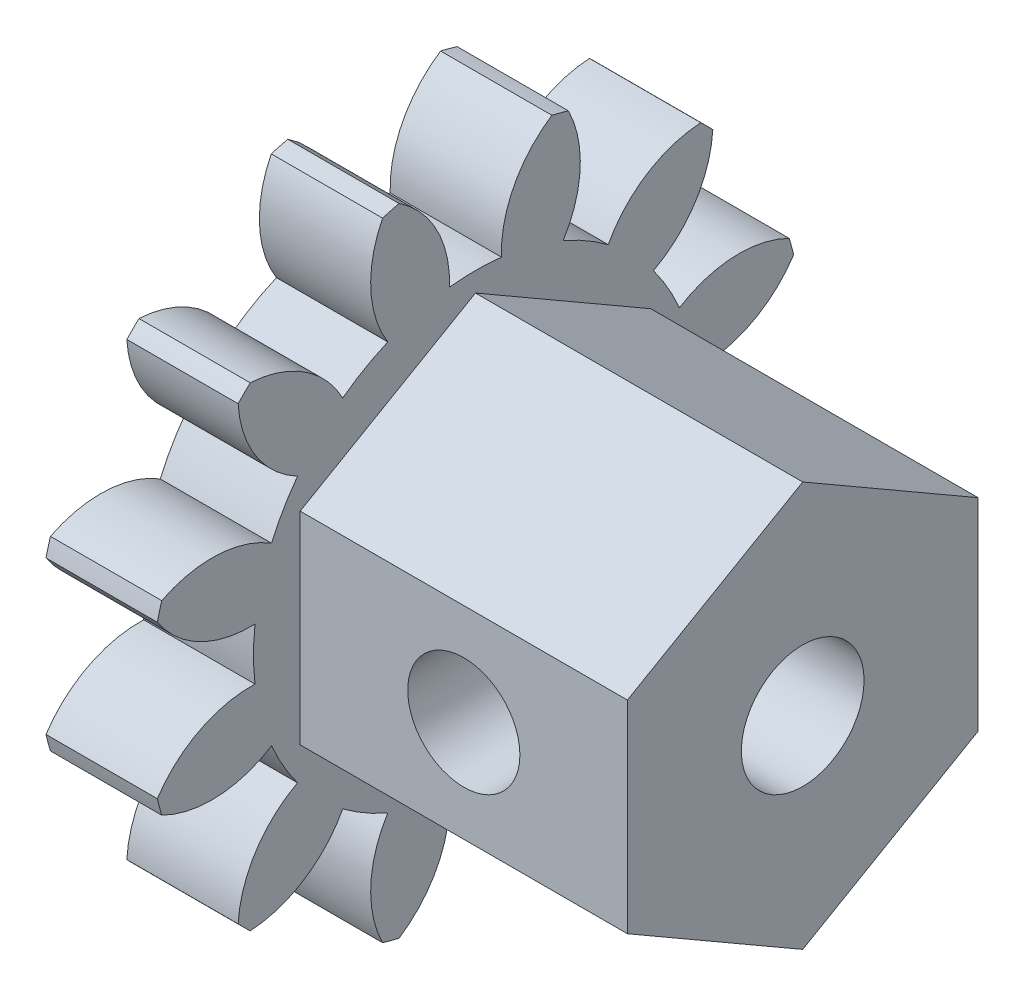
SolidWorks part; units mm, degrees
ref_plane "Plane1" through (0, 0, 0) normal (0, 0, 1) x (1, 0, 0)
ref_plane "Plane2" through (0, 0, 0) normal (0, 1, 0) x (1, 0, 0)
ref_plane "Plane3" through (0, 0, 0) normal (1, 0, 0) x (0, 0, -1)
sketch "HoldingSke" plane through (0, 0, 0) normal (0, 1, 0) x (1, 0, 0)
  line L0 (0, 0) -> (0.4891, -0.104)
  line L1 (-15, 0) -> (100, 0) construction
  line L2 (0, 0) -> (-2.1039, 2.3779)
  line L3 (0, 0) -> (-11.863, 4.5341)
  line L4 (0, 0) -> (8.4473, 1.7955)
  line L5 (0, 0) -> (-46.8476, -17.4728)
  line L6 (0, 0) -> (-3.9479, -2.6637)
  line L7 (-2.1039, 2.3779) -> (8.6586, 51.2059)
  line L8 (-76.2, 54.61) -> (-74.4, 54.61)
  line L9 (-71.009, 38.7566) -> (-53.1078, 45.2721)
  line L10 (-76.2, 71.12) -> (104.1128, 71.12)
  line L11 (0, 0) -> (-4.7625, 0)
  line L12 (-76.2, 101.6) -> (-76.133, 101.6)
  line L13 (24.9733, 27.94) -> (52.9518, 28.4284)
  line L14 (24.9733, 27.94) -> (24.9743, 27.94)
  line L15 (24.9733, 27.94) -> (100.4006, 29.5858)
  line L16 (-63.627, -2) -> (-12.827, -2)
  circle A0 centre (0, 0) radius 5
  circle A1 centre (0, 0) radius 9.499
  circle A2 centre (0, 0) radius 37.5
  circle A3 centre (0, 0) radius 5
  dimension "MHD" = 18.998
  dimension "Hub_dia" = 75
  dimension "Bore" = 10
  dimension "MBD" = 10
  dimension "Num_teeth" = 12
  dimension "Pitch_radius" = 180.3128
  dimension "Pitch" = 0.5
  dimension "Width" = 4.7625
  dimension "Overall_len" = 50
  dimension "Show_teeth" = 12
  dimension "Thickness" = 4.7625
  dimension "OAL" = 50.0001
  dimension "T_dim" = 1.8
  dimension "Ap" = 20
  dimension "H" = 19.05
  dimension "Backlash" = 0.067
  dimension "Addendum_fac" = 1
  dimension "Dedendum_fac" = 1.25
  dimension "Clearance_fac" = 0.25
  dimension "Dedendum_add" = 0.001
  dimension "Module" = 2
sketch "BasProSke" plane through (0, 0, 0) normal (0, 1, 0) x (1, 0, 0)
  line L0 (-10, 0) -> (60, 0) construction
  line L1 (0, 0) -> (0, 14)
  line L2 (0, 0) -> (4.7625, 0)
  line L3 (4.7625, 0) -> (4.7625, 14)
  line L4 (4.7625, 14) -> (0, 14)
  dimension "Diameter" = 28
  dimension "Thickness" = 4.7625
revolve "Base-Revolve" add sketch "BasProSke" angle 360 about L0
sketch "TooCutSke" plane through (0, 0, 0) normal (1, 0, 0) x (0, 0, -1)
  line L1 (0, 0) -> (0, 107) construction
  line L2 (0, 0) -> (-1.6834, 11.8813) construction
  line L3 (0, 0) -> (-6.1662, 23.0126) construction
  line L4 (-1.6834, 11.8813) -> (-3.0831, 11.5063) construction
  arc A0 (1.1119, 9.4337) -> (-1.1119, 9.4337) centre (0, 0) ccw
  arc A1 (3.2981, 13.6321) -> (-3.2981, 13.6321) centre (0, 0) ccw
  circle A2 centre (0, 0) radius 12 construction
  circle A3 centre (0, 0) radius 11.2763 construction
  arc A4 (-1.1119, 9.4337) -> (-3.2981, 13.6321) centre (-5.9089, 9.6042) ccw
  arc A5 (3.2981, 13.6321) -> (1.1119, 9.4337) centre (5.9089, 9.6042) ccw
  dimension "Root_dia" = 18.998
  dimension "Overcut_dia" = 28.0508
  dimension "Pitch_dia" = 24
  dimension "Base_dia" = 22.5526
  dimension "Flank_rad" = 4.8
  dimension "Half_ang" = 15
  dimension "Half_CT" = 1.4491
extrude "ToothCut" cut sketch "TooCutSke" along normal through all
fillet "Breaks" [suppressed] radius 0.04
fillet "RootFillets" [suppressed] radius 0.501
pattern_circular "TeethCuts" count 12 every 30 about axis through (-10, 0, 0) along (1, 0, 0) of "ToothCut", "RootFillets", "Breaks"
sketch "HubNeaOneSke" plane through (0, 0, 0) normal (-1, 0, 0) x (0, 0, 1)
  circle A0 centre (0, 0) radius 9.499
  dimension "Diameter" = 18.998
extrude "HubNearOne" [suppressed] add sketch "HubNeaOneSke" along normal blind 45.2376
sketch "HubNeaBotSke" plane through (0, 0, 0) normal (-1, 0, 0) x (0, 0, 1)
  circle A0 centre (0, 0) radius 9.499
  dimension "Diameter" = 18.998
extrude "HubNearBoth" [suppressed] add sketch "HubNeaBotSke" along normal blind 22.6188
ref_plane "FarPln" through (4.7625, 0, 0) normal (1, 0, 0) x (0, 0, -1)
sketch "HubFarSke" plane through (4.7625, 0, 0) normal (1, 0, 0) x (0, 0, -1)
  circle A0 centre (0, 0) radius 9.499
  dimension "Diameter" = 18.998
extrude "HubFar" [suppressed] add sketch "HubFarSke" along normal blind 22.6188
sketch "BorSke" plane through (0, 0, 0) normal (1, 0, 0) x (0, 0, -1)
  circle A0 centre (0, 0) radius 2.625
  dimension "Diameter" = 5.25
extrude "Bore" cut sketch "BorSke" along normal mid plane 100.0001
sketch "KeySke" plane through (0, 0, 0) normal (1, 0, 0) x (0, 0, -1)
  line L0 (-2, 0) -> (-2, 6.8)
  line L1 (-2, 6.8) -> (2, 6.8)
  line L2 (2, 6.8) -> (2, 0)
  line L3 (0, 0) -> (0, 34) construction
  line L4 (-2, 0) -> (2, 0)
  dimension "Offset" = 6.8
  dimension "Width" = 4
extrude "Keyway" [suppressed] cut sketch "KeySke" along normal mid plane 100.0001
pattern_circular "Keyway2" [suppressed] count 2 every 90 about axis through (-10, 0, 0) along (1, 0, 0)
sketch "Sketch1" plane through (4.7625, 0, 0) normal (1, 0, 0) x (0, 0, -1)
  line L1 (0, 8.6603) -> (-7.5, 4.3301)
  line L2 (-7.5, 4.3301) -> (-7.5, -4.3301)
  line L3 (-7.5, -4.3301) -> (0, -8.6603)
  line L4 (0, -8.6603) -> (7.5, -4.3301)
  line L5 (7.5, -4.3301) -> (7.5, 4.3301)
  line L6 (7.5, 4.3301) -> (0, 8.6603)
  circle A0 centre (0, 0) radius 7.5 construction
  dimension "D1" = 15
extrude "Boss-Extrude1" add sketch "Sketch1" along normal blind 14
sketch "Sketch2" plane through (18.7625, 0, 0) normal (1, 0, 0) x (0, 0, -1)
  circle A0 centre (0, 0) radius 2.625 construction
  circle A1 centre (0, 0) radius 2.625
extrude "Cut-Extrude1" cut sketch "Sketch2" against normal through all
sketch "Sketch3" plane through (0, 0, 7.5) normal (0, 0, 1) x (1, 0, 0)
  line L0 (18.7625, 0) -> (4.7625, 0) construction
  line L3 (18.7625, 4.3301) -> (18.7625, -4.3301) construction
  line L4 (4.7625, -1.1119) -> (4.7625, 1.1119) construction
  circle A0 centre (11.7625, 0) radius 2.4
  dimension "D1" = 4.8
extrude "Cut-Extrude2" cut sketch "Sketch3" against normal through all
equation "' \"Module@HoldingSke\" = 6.35"
equation "' \"Num_teeth@HoldingSke\" = 12"
equation "' \"Ap@HoldingSke\" =  20"
equation "' \"Width@HoldingSke\" = 0.5 * 25.4"
equation "' \"Hub_dia@HoldingSke\"= 1 * 25.4"
equation "' \"Overall_len@HoldingSke\" = 1.0 * 25.4"
equation "' \"Bore@HoldingSke\" = 0.75 * 25.4"
equation "' \"T_dim@HoldingSke\" = 0.1 * 25.4"
equation "' \"Width@KeySke\" = 0.25 * 25.4"
equation "' \"Show_teeth@HoldingSke\" = 13"
equation "' \"Backlash@HoldingSke\" = 0.009 * 25.4"
equation "' \"Addendum_fac@HoldingSke\" = 1.0"
equation "' \"Dedendum_fac@HoldingSke\" = 1.25"
equation "' \"Dedendum_add@HoldingSke\" = 0.00005 * 25.4"
equation "' \"Clearance_fac@HoldingSke\" = 0.25"
equation "\"Pitch@HoldingSke\" = 1 / \"Module@HoldingSke\""
equation "\"Overcut_dia@TooCutSke\" = (\"Num_teeth@HoldingSke\" + 2 * \"Addendum_fac@HoldingSke\") / \"Pitch@HoldingSke\" + 0.002 * 25.4"
equation "\"Pitch_dia@TooCutSke\" = \"Num_teeth@HoldingSke\" / \"Pitch@HoldingSke\""
equation "\"Base_dia@TooCutSke\" = \"Num_teeth@HoldingSke\" / \"Pitch@HoldingSke\" * cos((\"Ap@HoldingSke\"  * 3.14159265 / 180))"
equation "\"Root_dia@TooCutSke\" = (\"Num_teeth@HoldingSke\" + 2) / \"Pitch@HoldingSke\" - 2 * (\"Addendum_fac@HoldingSke\" + \"Dedendum_fac@HoldingSke\") / \"Pitch@HoldingSke\" - \"Dedendum_add@HoldingSke\" * 2"
equation "\"Half_ang@TooCutSke\" = 180 / \"Num_teeth@HoldingSke\""
equation "\"Half_CT@TooCutSke\" = \"Num_teeth@HoldingSke\" / \"Pitch@HoldingSke\" * sin((3.14159265 / 2 / \"Num_teeth@HoldingSke\")) / 2 - 7 * \"Backlash@HoldingSke\" / 4"
equation "\"Flank_rad@TooCutSke\" = \"Num_teeth@HoldingSke\" / \"Pitch@HoldingSke\" / 5"
equation "\"Radius@RootFillets\" = \"Clearance_fac@HoldingSke\" / \"Pitch@HoldingSke\" + \"Dedendum_add@HoldingSke\""
equation "\"Break_rad@Breaks\" = 0.02 / \"Pitch@HoldingSke\""
equation "\"Thickness@HoldingSke\" = \"Width@HoldingSke\""
equation "\"OAL@HoldingSke\" = \"Thickness@HoldingSke\""
equation "\"MHD@HoldingSke\" = (\"Num_teeth@HoldingSke\" + 2) / \"Pitch@HoldingSke\" - 2 * (\"Addendum_fac@HoldingSke\" + \"Dedendum_fac@HoldingSke\")  / \"Pitch@HoldingSke\" - \"Dedendum_add@HoldingSke\" * 2"
equation "\"MBD@HoldingSke\" = (\"Num_teeth@HoldingSke\" + 2) / \"Pitch@HoldingSke\" - 2 * (\"Addendum_fac@HoldingSke\" + \"Dedendum_fac@HoldingSke\")  / \"Pitch@HoldingSke\" - \"Dedendum_add@HoldingSke\" * 2 - 0.002 * 25.4"
equation "\"MHD@HoldingSke\" = ((sgn( \"MHD@HoldingSke\" - \"Hub_dia@HoldingSke\" )-1)*( \"MHD@HoldingSke\" - \"Hub_dia@HoldingSke\" ))/-2+ \"Hub_dia@HoldingSke\""
equation "\"MBD@HoldingSke\" = ((sgn( \"MBD@HoldingSke\" - \"Bore@HoldingSke\" )-1)*( \"MBD@HoldingSke\" - \"Bore@HoldingSke\" ))/-2+ \"Bore@HoldingSke\""
equation "\"OAL@HoldingSke\" = ((sgn( \"OAL@HoldingSke\" - \"Overall_len@HoldingSke\" )+1)*( \"OAL@HoldingSke\" - \"Overall_len@HoldingSke\" ))/2 + \"Overall_len@HoldingSke\" + 0.000002 * 25.4"
equation "\"Num_teeth@TeethCuts\" = int( \"Show_teeth@HoldingSke\" ) + 1"
equation "\"Num_teeth@TeethCuts\" = ((sgn( \"Num_teeth@TeethCuts\" - \"Num_teeth@HoldingSke\" )-1)*( \"Num_teeth@TeethCuts\" - \"Num_teeth@HoldingSke\" ))/-2+ \"Num_teeth@HoldingSke\""
equation "\"Num_teeth@TeethCuts\" = ((sgn( \"Num_teeth@TeethCuts\" - 2.0)+1)*( \"Num_teeth@TeethCuts\" - 2.0))/2 +2.0"
equation "\"Angle@TeethCuts\" = 360.0 / \"Num_teeth@HoldingSke\""
equation "\"Diameter@BasProSke\" = (\"Num_teeth@HoldingSke\" + 2 * \"Addendum_fac@HoldingSke\") / \"Pitch@HoldingSke\""
equation "\"Thickness@BasProSke\"  = \"Thickness@HoldingSke\""
equation "' \"Fillet_rad@BasProSke\" =  \"Thickness@HoldingSke\" * 0.05"
equation "\"MHD@HoldingSke\" = ((sgn( \"MHD@HoldingSke\" - \"Root_dia@TooCutSke\" )-1)*( \"MHD@HoldingSke\" - \"Root_dia@TooCutSke\" ))/-2+ \"Root_dia@TooCutSke\""
equation "\"Diameter@HubNeaOneSke\" = \"MHD@HoldingSke\""
equation "\"Length@HubNearOne\" = \"OAL@HoldingSke\" - \"Thickness@BasProSke\""
equation "\"Diameter@HubNeaBotSke\" = \"MHD@HoldingSke\""
equation "\"Length@HubNearBoth\" = ( \"OAL@HoldingSke\" - \"Thickness@BasProSke\" ) / 2.0"
equation "\"Thickness@FarPln\" = \"Thickness@BasProSke\""
equation "\"Diameter@HubFarSke\" = \"MHD@HoldingSke\""
equation "\"Length@HubFar\" = ( \"OAL@HoldingSke\" - \"Thickness@BasProSke\" ) / 2.0"
equation "\"D1@Bore\" = \"OAL@HoldingSke\" * 2.0"
equation "\"D1@Keyway\" = \"OAL@HoldingSke\" * 2.0"
equation "\"Offset@KeySke\" = \"T_dim@HoldingSke\" + \"MBD@HoldingSke\" / 2.0"
